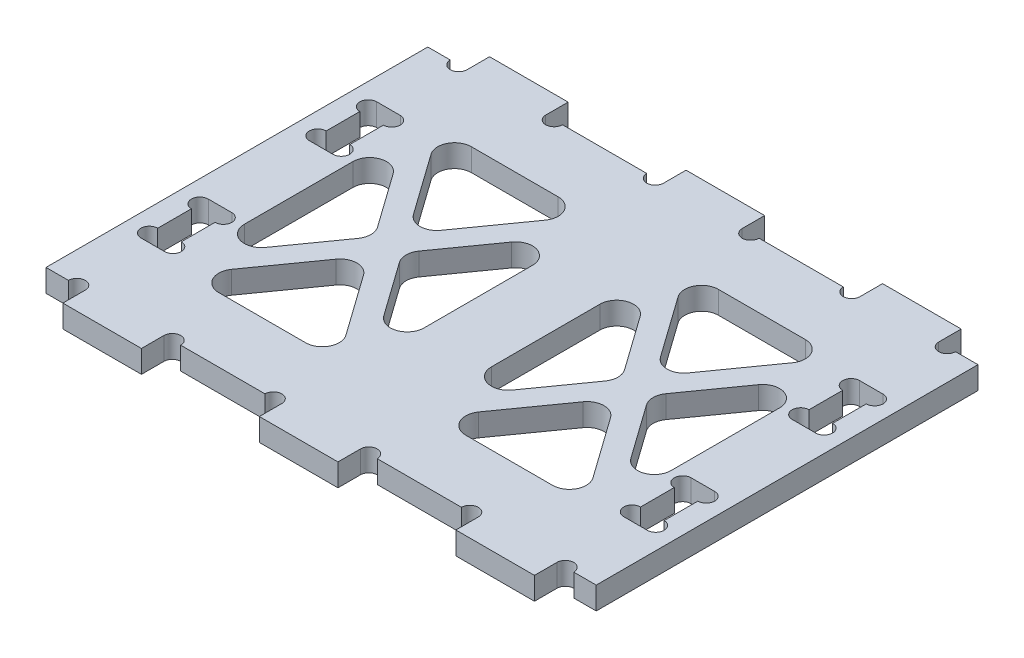
SolidWorks part; units mm, degrees
ref_plane "前视基准面" through (0, 0, 0) normal (0, 0, 1) x (1, 0, 0)
ref_plane "上视基准面" through (0, 0, 0) normal (0, 1, 0) x (1, 0, 0)
ref_plane "右视基准面" through (0, 0, 0) normal (1, 0, 0) x (0, 0, -1)
other "Configuration Table"
sketch "草图1" plane through (0, 0, 0) normal (0, 1, 0) x (1, 0, 0)
  line L0 (0, 30.6829) -> (0, -37.3171) construction
  line L1 (-49, -34) -> (49, -34)
  line L2 (-49, -34) -> (-49, 34)
  line L3 (-49, 34) -> (49, 34)
  line L4 (49, -34) -> (49, 34)
  line L5 (-49, -34) -> (49, 34) construction
  line L6 (-49, 34) -> (49, -34) construction
  line L7 (28, 38) -> (28, 34)
  line L8 (-7, 38) -> (7, 38)
  line L9 (-7, 38) -> (-7, 34)
  line L10 (-7, 34) -> (7, 34)
  line L11 (7, 38) -> (7, 34)
  line L12 (-7, 38) -> (7, 34) construction
  line L13 (-7, 34) -> (7, 38) construction
  line L14 (28, 38) -> (42, 38)
  line L15 (42, 38) -> (42, 34)
  line L16 (-42, 38) -> (-42, 34)
  line L17 (-28, 38) -> (-42, 38)
  line L18 (-28, 38) -> (-28, 34)
  line L19 (-49, 0) -> (49, 0) construction
  line L20 (42, -38) -> (42, -34)
  line L21 (28, -38) -> (42, -38)
  line L22 (28, -38) -> (28, -34)
  line L23 (-7, -34) -> (7, -38) construction
  line L24 (-7, -38) -> (7, -34) construction
  line L25 (7, -38) -> (7, -34)
  line L26 (-7, -38) -> (-7, -34)
  line L27 (-7, -38) -> (7, -38)
  line L28 (-28, -38) -> (-28, -34)
  line L29 (-28, -38) -> (-42, -38)
  line L30 (-42, -38) -> (-42, -34)
  point P0 (0, 0)
  point P7 (0, 36)
  point P31 (0, -36)
  dimension "D1" = 98
  dimension "D2" = 68
  dimension "D3" = 4
  dimension "D4" = 14
  dimension "D6" = 35
  dimension "D5" = 2
extrude "凸台-拉伸1" add sketch "草图1" along normal blind 4 contours L30 L29 L28 L1 | L1 L4 L3 L2 | L26 L27 L25 L1 | L22 L21 L20 L1 | L18 L17 L16 L3 | L15 L14 L7 L3 | L9 L8 L11 L10
sketch "草图2" plane through (0, 4, 0) normal (0, 1, 0) x (1, 0, 0)
  line L0 (-49, 34) -> (-42, 34) construction
  line L1 (-28, 34) -> (-7, 34) construction
  line L2 (-49, -34) -> (-42, -34) construction
  line L4 (-28, -34) -> (-7, -34) construction
  line L5 (7, 34) -> (28, 34) construction
  line L6 (7, -34) -> (28, -34) construction
  line L7 (42, -34) -> (49, -34) construction
  line L8 (42, 34) -> (49, 34) construction
  circle A0 centre (-43.5, 34) radius 1.5
  circle A1 centre (-26.5, 34) radius 1.5
  circle A2 centre (-8.5, 34) radius 1.5
  circle A3 centre (-43.5, -34) radius 1.5
  circle A5 centre (-26.5, -34) radius 1.5
  circle A6 centre (-8.5, -34) radius 1.5
  circle A7 centre (8.5, 34) radius 1.5
  circle A8 centre (26.5, 34) radius 1.5
  circle A9 centre (26.5, -34) radius 1.5
  circle A10 centre (8.5, -34) radius 1.5
  circle A11 centre (43.5, -34) radius 1.5
  circle A12 centre (43.5, 34) radius 1.5
  dimension "D1" = 3
extrude "切除-拉伸1" cut sketch "草图2" against normal blind 4
sketch "草图3" plane through (0, 4, 0) normal (0, 1, 0) x (1, 0, 0)
  line L0 (49, 0) -> (0, 0) construction
  line L1 (49, -34) -> (49, 34) construction
  line L2 (43, 21) -> (43, 9) construction
  line L3 (40.9, 21) -> (45.1, 21)
  line L4 (40.9, 21) -> (40.9, 9)
  line L5 (40.9, 9) -> (45.1, 9)
  line L6 (45.1, 21) -> (45.1, 9)
  line L7 (43, -21) -> (43, -9) construction
  line L8 (45.1, -21) -> (45.1, -9)
  line L9 (40.9, -9) -> (45.1, -9)
  line L10 (40.9, -21) -> (40.9, -9)
  line L11 (40.9, -21) -> (45.1, -21)
  circle A0 centre (40.9, 19.5) radius 1.5
  circle A1 centre (45.1, 19.5) radius 1.5
  circle A2 centre (40.9, 10.5) radius 1.5
  circle A3 centre (45.1, 10.5) radius 1.5
  circle A4 centre (45.1, -10.5) radius 1.5
  circle A5 centre (40.9, -10.5) radius 1.5
  circle A6 centre (45.1, -19.5) radius 1.5
  circle A7 centre (40.9, -19.5) radius 1.5
  dimension "D4" = 3
  dimension "D1" = 6
  dimension "D2" = 12
  dimension "D3" = 4.2
  dimension "D5" = 18
extrude "切除-拉伸2" cut sketch "草图3" against normal blind 10 contours A3 L6 A1 L3 A0 L4 A2 L5 | L4 A2 | L4 A2 | L4 A0 | L4 A0 | L6 A1 | L6 A1 | L6 A3 | L6 A3 | A7 L10 | A7 L10 | L10 A7 L11 A6 L8 A4 L9 A5 | A6 L8 | A5 L10 | A4 L8 | A4 L8 | A6 L8 | A5 L10
mirror "镜向1" about plane through (0, 0, 0) normal (1, 0, 0) of "切除-拉伸2"
sketch "草图4" plane through (0, 4, 0) normal (0, 1, 0) x (1, 0, 0)
  line L0 (36.5339, 0) -> (-36.5339, 0) construction
  line L1 (0, 0) -> (0, 23.6472) construction
  line L2 (-38, 22.5) -> (-6, -22.5) construction
  line L3 (-38, 22.5) -> (-6, 22.5)
  line L4 (-38, 22.5) -> (-38, -22.5)
  line L5 (-38, -22.5) -> (-6, -22.5)
  line L6 (-6, 22.5) -> (-6, -22.5)
  line L7 (-6, 22.5) -> (-38, -22.5) construction
  line L8 (-35.5459, 22.5) -> (-6, -19.0489)
  line L9 (-38, 19.0489) -> (-8.4541, -22.5)
  line L10 (-38, 22.5) -> (-22, 0)
  line L11 (-22, 0) -> (-38, -22.5)
  line L12 (-8.4541, 22.5) -> (-38, -19.0489)
  line L13 (-6, 19.0489) -> (-35.5459, -22.5)
  line L14 (6, 22.5) -> (38, -22.5) construction
  line L15 (38, 22.5) -> (6, -22.5) construction
  line L16 (6, 19.0489) -> (35.5459, -22.5)
  line L17 (8.4541, 22.5) -> (38, -19.0489)
  line L18 (22, 0) -> (38, -22.5)
  line L19 (38, 22.5) -> (22, 0)
  line L20 (38, 19.0489) -> (8.4541, -22.5)
  line L21 (35.5459, 22.5) -> (6, -19.0489)
  line L22 (6, 22.5) -> (6, -22.5)
  line L23 (38, -22.5) -> (6, -22.5)
  line L24 (38, 22.5) -> (38, -22.5)
  line L25 (38, 22.5) -> (6, 22.5)
  dimension "D1" = 45
  dimension "D2" = 32
  dimension "D3" = 4
  dimension "D4" = 4
  dimension "D5" = 2
  dimension "D6" = 2
  dimension "D7" = 12
extrude "切除-拉伸3" cut sketch "草图4" against normal blind 5 contours L12 L9 L4 | L12 L3 L8 | L6 L13 L8 | L9 L13 L5 | L16 L22 L21 | L21 L25 L17 | L24 L20 L17 | L23 L16 L20
fillet "圆角1" radius 3 24 edges at (8.4541, 2, 22.5) (35.5459, 2, 22.5) (38, 2, 19.0489) (38, 2, -19.0489) (24.4541, 2, 0) (22, 2, 3.4511) (22, 2, -3.4511) (35.5459, 2, -22.5) (8.4541, 2, -22.5) (6, 2, 19.0489) (19.5459, 2, 0) (6, 2, -19.0489) (-8.4541, 2, 22.5) (-35.5459, 2, 22.5) (-38, 2, 19.0489) (-6, 2, -19.0489) (-8.4541, 2, -22.5) (-35.5459, 2, -22.5) (-22, 2, 3.4511) (-19.5459, 2, 0) (-22, 2, -3.4511) (-24.4541, 2, 0) (-38, 2, -19.0489) (-6, 2, 19.0489)
